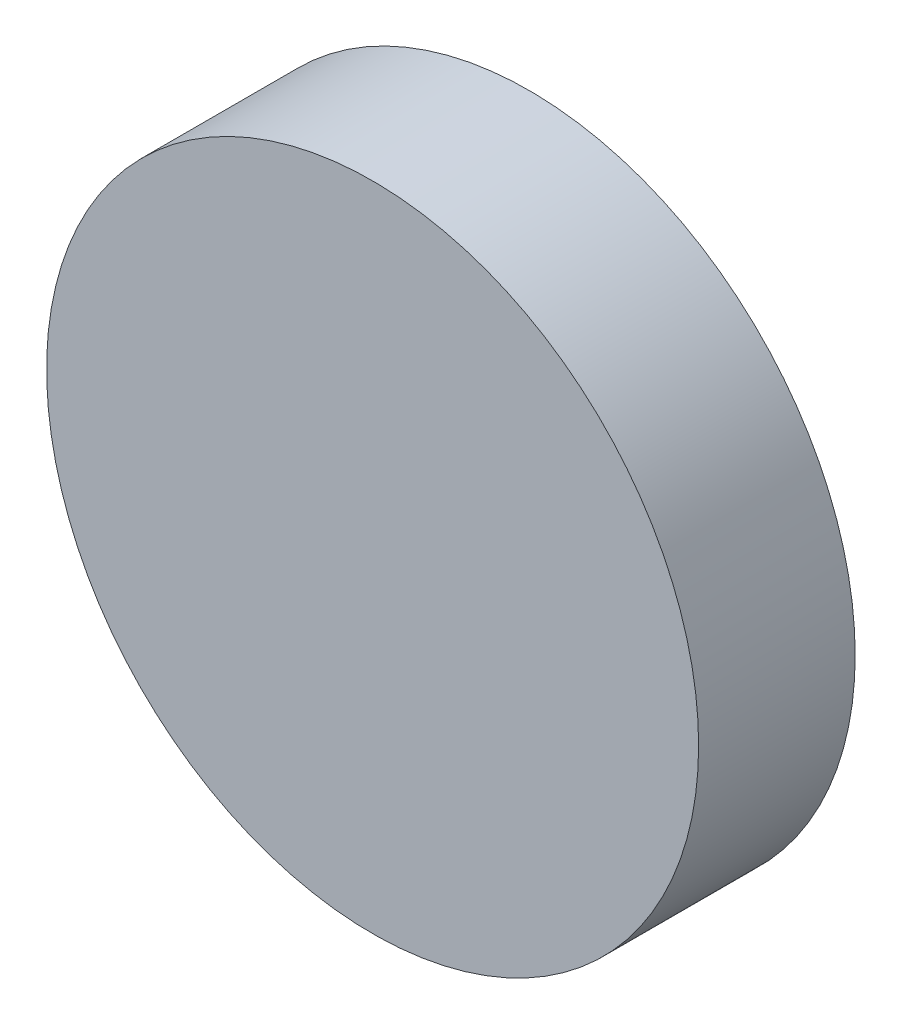
SolidWorks part; units mm, degrees
ref_plane "Plano frontal" through (0, 0, 0) normal (0, 0, 1) x (1, 0, 0)
ref_plane "Plano superior" through (0, 0, 0) normal (0, 1, 0) x (1, 0, 0)
ref_plane "Plano direito" through (0, 0, 0) normal (1, 0, 0) x (0, 0, -1)
sketch "Esboço1" plane through (0, 0, 0) normal (0, 0, 1) x (1, 0, 0)
  circle A0 centre (0, 0) radius 17.075
  dimension "D1" = 34.15
extrude "Ressalto-extrusão1" add sketch "Esboço1" along normal blind 8.2
sketch "Esboço2" plane through (0, 0, 0) normal (0, 0, -1) x (-1, 0, 0)
  circle A0 centre (0, 0) radius 8.85
  dimension "D1" = 17.7
extrude "Corte-extrusão1" cut sketch "Esboço2" against normal blind 5
